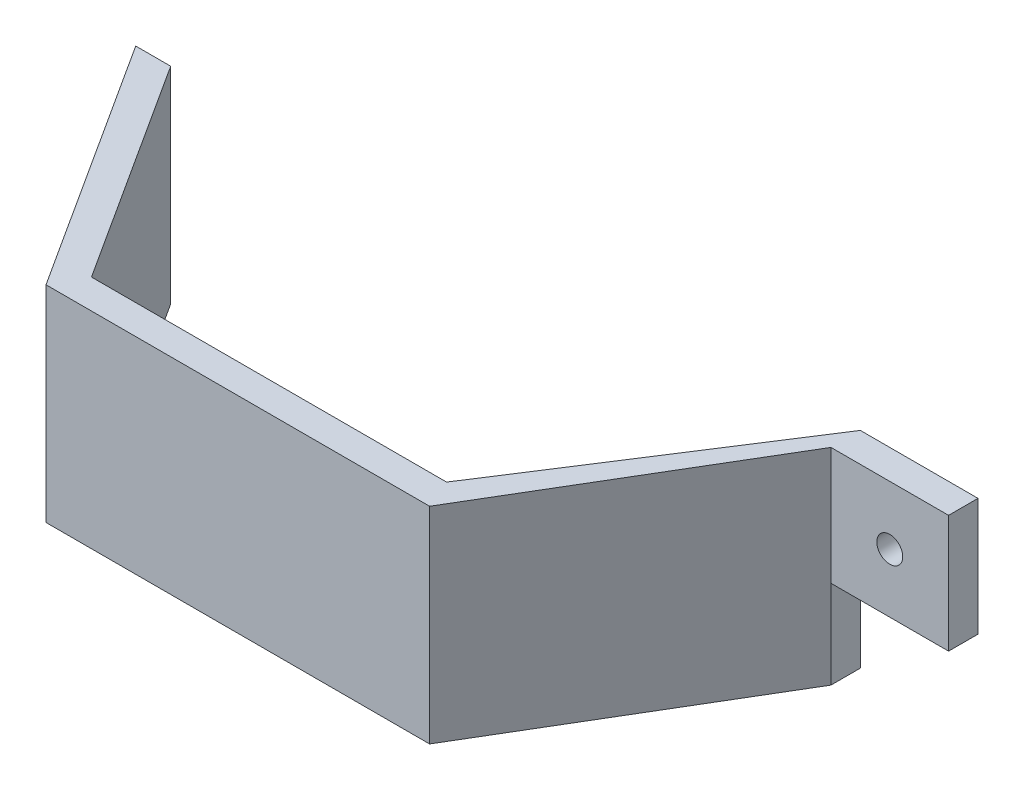
SolidWorks part; units mm, degrees
ref_plane "Plan de face" through (0, 0, 0) normal (0, 0, 1) x (1, 0, 0)
ref_plane "Plan de dessus" through (0, 0, 0) normal (0, 1, 0) x (1, 0, 0)
ref_plane "Plan de droite" through (0, 0, 0) normal (1, 0, 0) x (0, 0, -1)
sketch "Esquisse2" plane through (0, 0, 0) normal (0, 0, 1) x (1, 0, 0)
  line L1 (-9.9497, 9.6985) -> (10.0503, 9.6985)
  line L2 (-9.9497, 9.6985) -> (-9.9497, -10.3015)
  line L3 (-9.9497, -10.3015) -> (10.0503, -10.3015)
  line L4 (10.0503, 9.6985) -> (10.0503, -10.3015)
  dimension "D1" = 20
  dimension "D2" = 20
extrude "Boss.-Extru.1" add sketch "Esquisse2" along normal blind 5
sketch "Esquisse3" plane through (0, 0, 5) normal (0, 0, 1) x (1, 0, 0)
  line L0 (10.0503, 9.6985) -> (-9.9497, 9.6985) construction
  line L2 (10.0503, -10.3015) -> (10.0503, 9.6985) construction
  circle A0 centre (0.0503, -0.3015) radius 2.2
  dimension "D1" = 10
  dimension "D2" = 10
extrude "Enlèv. mat.-Extru.1" cut sketch "Esquisse3" against normal blind 5
sketch "Esquisse4" plane through (0, 9.6985, 0) normal (0, 1, 0) x (1, 0, 0)
  line L0 (-9.9497, -5) -> (-35.3985, -47.7752)
  line L1 (-35.3985, -47.7752) -> (-100.607, -47.7752)
  line L2 (-100.607, -47.7752) -> (-128.1288, -5)
  line L3 (-128.1288, -5) -> (-122.1833, -5)
  line L4 (-122.1833, -5) -> (-97.8785, -42.7752)
  line L5 (-97.8785, -42.7752) -> (-37.5113, -42.7752)
  line L6 (-37.5113, -42.7752) -> (-9.9497, 0)
  line L7 (-9.9497, 0) -> (-9.9497, -5)
  dimension "D1" = 5
  dimension "D2" = 5
extrude "Boss.-Extru.2" add sketch "Esquisse4" against normal blind 35
